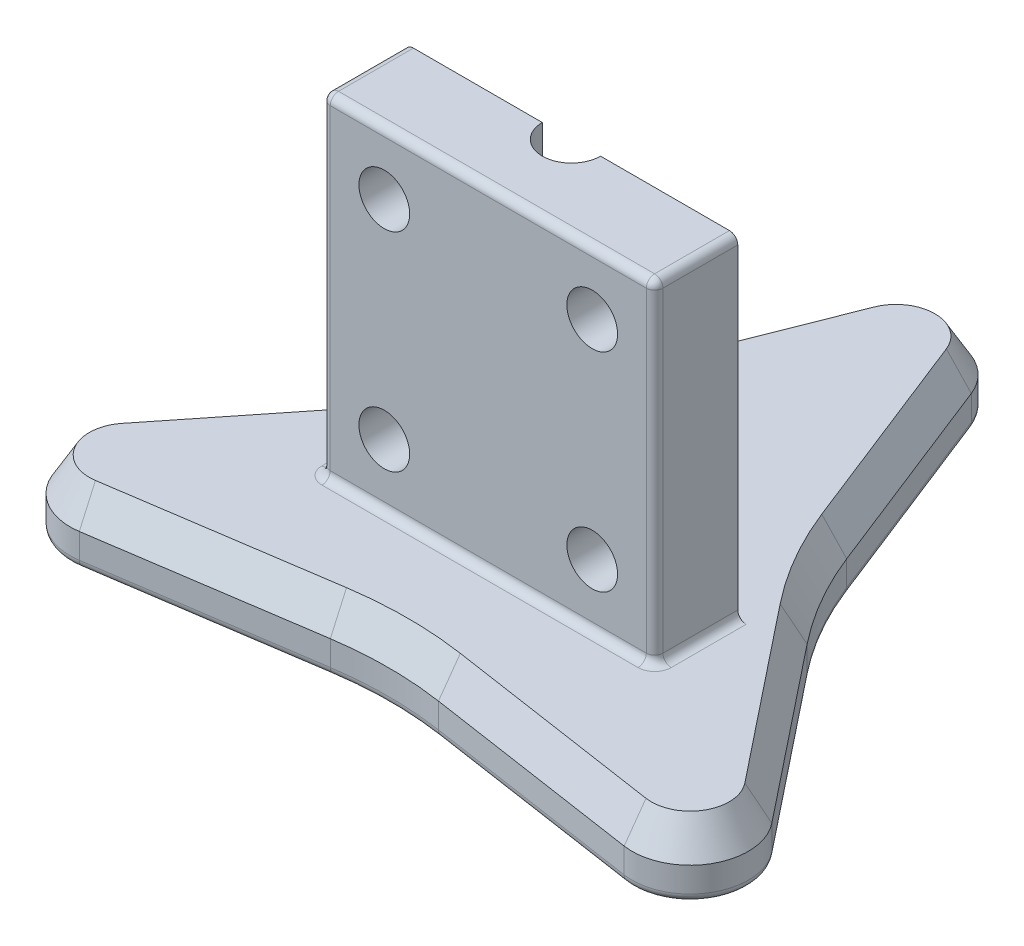
SolidWorks part; units mm, degrees
ref_plane "Front Plane" through (0, 0, 0) normal (0, 0, 1) x (1, 0, 0)
ref_plane "Top Plane" through (0, 0, 0) normal (0, 1, 0) x (1, 0, 0)
ref_plane "Right Plane" through (0, 0, 0) normal (1, 0, 0) x (0, 0, -1)
sketch "Sketch1" plane through (0, 0, 0) normal (0, 1, 0) x (1, 0, 0)
  line L0 (0, 0) -> (-68.3868, -39.4831) construction
  line L1 (0, 0) -> (0, 74.7926) construction
  line L2 (0, 0) -> (79.4724, -45.8834) construction
  line L3 (-6.5, 41.5729) -> (-16.2217, 16.8712)
  line L4 (6.5, 41.5729) -> (16.2217, 16.8712)
  line L5 (39.2532, -15.1573) -> (22.7217, 5.6128)
  line L6 (32.7532, -26.4156) -> (6.5, -22.484)
  line L7 (-32.7532, -26.4156) -> (-6.5, -22.484)
  line L8 (-39.2532, -15.1573) -> (-22.7217, 5.6128)
  arc A1 (-6.5, 41.5729) -> (6.5, 41.5729) centre (0, 39.0147) cw
  arc A2 (-16.2217, 16.8712) -> (-19.0526, 11) centre (-57.0604, 32.9438) cw
  arc A3 (16.2217, 16.8712) -> (19.0526, 11) centre (57.0604, 32.9438) ccw
  arc A4 (39.2532, -15.1573) -> (32.7532, -26.4156) centre (33.7877, -19.5074) cw
  arc A5 (22.7217, 5.6128) -> (19.0526, 11) centre (57.0604, 32.9438) cw
  arc A6 (6.5, -22.484) -> (0, -22) centre (0, -65.8877) ccw
  arc A7 (-32.7532, -26.4156) -> (-39.2532, -15.1573) centre (-33.7877, -19.5074) cw
  arc A8 (-6.5, -22.484) -> (0, -22) centre (0, -65.8877) cw
  arc A9 (-22.7217, 5.6128) -> (-19.0526, 11) centre (-57.0604, 32.9438) ccw
  dimension "D3" = 22
  dimension "D6" = 6.9853
  dimension "D4" = 39.0147
  dimension "D1" = 60
  dimension "D2" = 60
  dimension "D5" = 6.5
  dimension "D7" = 6.5
extrude "Extrude2" add sketch "Sketch1" along normal blind 8
chamfer "Chamfer2" distance 4 angle 30 12 edges at (11.3609, 8, -29.222) (0, 8, -46) (19.0526, 8, -11) (-11.3609, 8, -29.222) (30.9874, 8, 4.7722) (-19.0526, 8, -11) (39.8372, 8, 23) (-30.9874, 8, 4.7722) (19.6266, 8, 24.4498) (-39.8372, 8, 23) (0, 8, 22) (-19.6266, 8, 24.4498)
sketch "Sketch2" plane through (0, 0, 0) normal (0, 1, 0) x (1, 0, 0)
  line L1 (173205.0808, 100000) -> (-173273.4675, -100039.4831) construction
  line L2 (-22.7213, -13.1182) -> (-42.235, -24.3844) construction
  arc A0 (-33.0698, -24.9603) -> (-38.1512, -16.1592) centre (-33.7877, -19.5074) cw
  arc A1 (-33.4614, -21.986) -> (-35.7711, -17.9855) centre (-33.7877, -19.5074) cw
  arc A2 (-38.1512, -16.1592) -> (-35.7711, -17.9855) centre (-36.9611, -17.0723) cw
  arc A3 (-33.0698, -24.9603) -> (-33.4614, -21.986) centre (-33.2656, -23.4731) ccw
  arc A4 (-5.0813, 41.1195) -> (5.0813, 41.1195) centre (0, 39.0147) cw
  arc A5 (-2.3097, 39.9714) -> (2.3097, 39.9714) centre (0, 39.0147) cw
  arc A6 (5.0813, 41.1195) -> (2.3097, 39.9714) centre (3.6955, 40.5454) cw
  arc A7 (-5.0813, 41.1195) -> (-2.3097, 39.9714) centre (-3.6955, 40.5454) ccw
  arc A8 (38.1512, -16.1592) -> (33.0698, -24.9603) centre (33.7877, -19.5074) cw
  arc A9 (35.7711, -17.9855) -> (33.4614, -21.986) centre (33.7877, -19.5074) cw
  arc A10 (33.0698, -24.9603) -> (33.4614, -21.986) centre (33.2656, -23.4731) cw
  arc A11 (38.1512, -16.1592) -> (35.7711, -17.9855) centre (36.9611, -17.0723) ccw
  dimension "D1" = 1.5
  dimension "D3" = 135
  dimension "D2" = 5.5
extrude "Cut-Extrude1" cut sketch "Sketch2" along normal blind 3
sketch "Sketch3" plane through (0, 0, 0) normal (0, 1, 0) x (1, 0, 0)
  line L0 (-20, 0) -> (-20, -10)
  line L1 (-20, -10) -> (20, -10)
  line L2 (0, -200000) -> (0, 200074.7926) construction
  line L3 (-20, 0) -> (-3.5, 0)
  line L4 (0, 0) -> (0, 9.9623) construction
  line L5 (20, 0) -> (3.5, 0)
  line L6 (20, 0) -> (20, -10)
  arc A0 (-3.5, 0) -> (3.5, 0) centre (0, 0) ccw
  point P13 (0, -10)
  dimension "D3" = 3.5
  dimension "D1" = 10
  dimension "D2" = 20
extrude "Extrude3" add sketch "Sketch3" along normal blind 40 from surface at 8 starting at face at (0, 8, 0)
sketch "Sketch4" plane through (0, 0, 0) normal (0, 0, 1) x (1, 0, 0)
  line L0 (-12.5, 40.5) -> (12.5, 40.5) construction
  line L1 (0, 0) -> (0, 55.9524) construction
  line L2 (-20, 48) -> (20, 48) construction
  circle A0 centre (-12.5, 40.5) radius 3.05
  circle A1 centre (12.5, 40.5) radius 3.05
  circle A2 centre (12.5, 15.5) radius 3.05
  circle A3 centre (-12.5, 15.5) radius 3.05
  point P11 (0, 40.5)
  dimension "D1" = 6.1
  dimension "D2" = 25
  dimension "D3" = 25
  dimension "D4" = 7.5
extrude "Cut-Extrude2" cut sketch "Sketch4" along normal through all
fillet "Fillet1" radius 1 20 edges at (20, 8, 5) (0, 8, 10) (39.8372, 0, 23) (19.6266, 0, 24.4498) (0, 0, 22) (-19.6266, 0, 24.4498) (-39.8372, 0, 23) (-30.9874, 0, 4.7722) (-19.0526, 0, -11) (-11.3609, 0, -29.222) (0, 0, -46) (11.3609, 0, -29.222) (19.0526, 0, -11) (30.9874, 0, 4.7722) (-20, 8, 5) (20, 48, 5) (-20, 48, 5) (-20, 28, 10) (20, 28, 10) (0, 48, 10)
